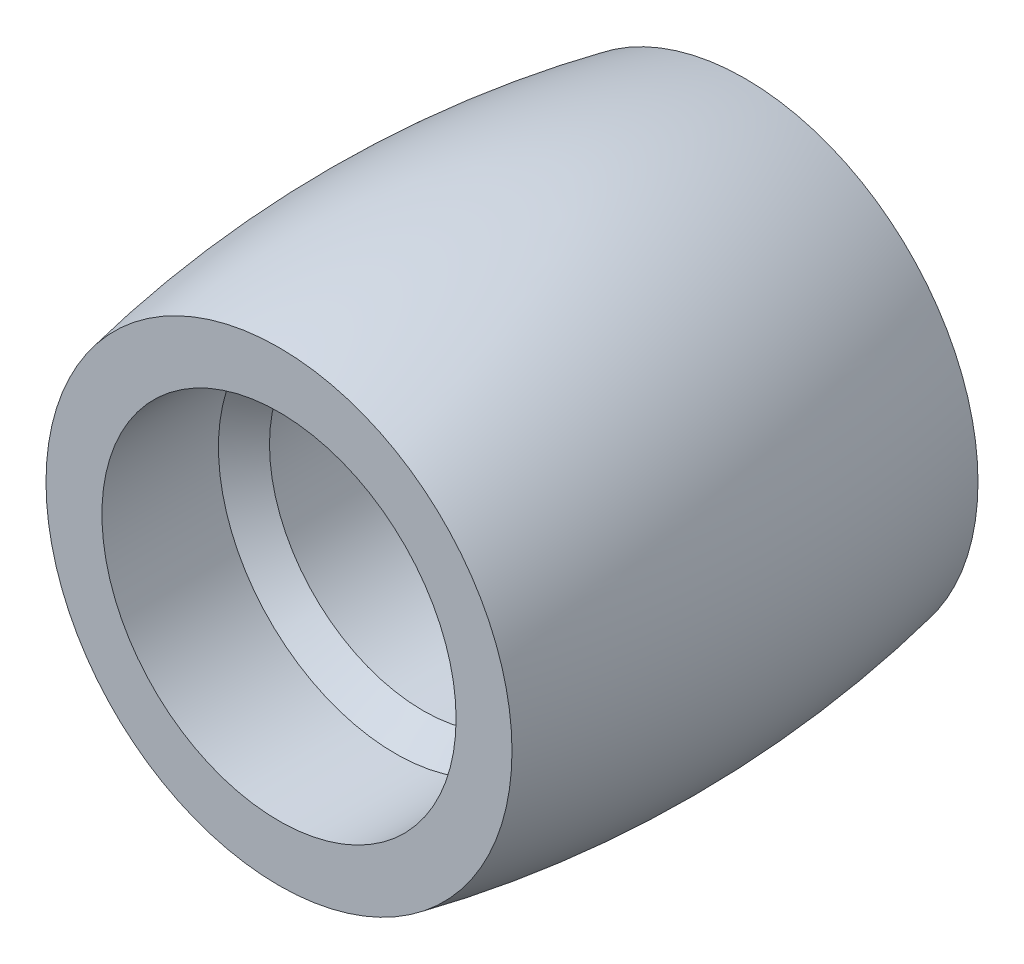
SolidWorks part; units mm, degrees
ref_plane "xy" through (0, 0, 0) normal (0, 0, 1) x (1, 0, 0)
ref_plane "xz" through (0, 0, 0) normal (0, 1, 0) x (1, 0, 0)
ref_plane "yz" through (0, 0, 0) normal (1, 0, 0) x (0, 0, -1)
sketch "Skizze4" plane through (0, 0, 0) normal (1, 0, 0) x (0, 0, -1)
  line L0 (-10, 0) -> (10, 0) construction
  line L1 (0, 11) -> (0, 6.6)
  line L3 (10, 10) -> (10, 7.6)
  line L4 (10, 7.6) -> (5, 7.6)
  line L5 (5, 7.6) -> (3.8082, 6.6)
  line L6 (3.8082, 6.6) -> (0, 6.6)
  arc A0 (0, 11) -> (10, 10) centre (0, -39.5) cw
  dimension "D1" = 20
  dimension "D2" = 15.2
  dimension "D3" = 22
  dimension "D4" = 1
  dimension "D5" = 40
  dimension "D6" = 5
  dimension "D7" = 1
revolve "Rotation1" add sketch "Skizze4" angle 360 about L0
mirror "Spiegeln2" about plane through (0, 0, 0) normal (0, 0, 1) of bodies 105
